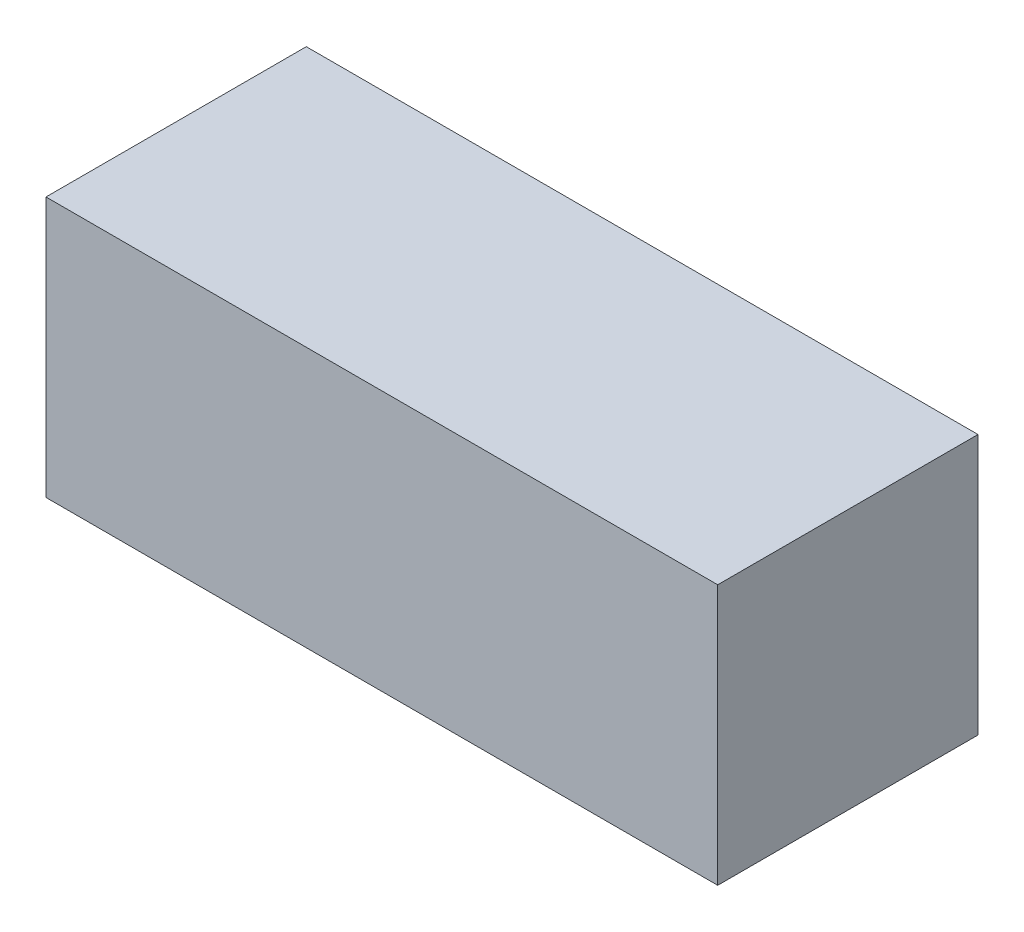
SolidWorks part; units mm, degrees
ref_plane "Front Plane" through (0, 0, 0) normal (0, 0, 1) x (1, 0, 0)
ref_plane "Top Plane" through (0, 0, 0) normal (0, 1, 0) x (1, 0, 0)
ref_plane "Right Plane" through (0, 0, 0) normal (1, 0, 0) x (0, 0, -1)
sketch "Sketch1" plane through (0, 0, 0) normal (0, 1, 0) x (1, 0, 0)
  line L1 (0, 1181.1) -> (6096, 1181.1)
  line L2 (0, 1181.1) -> (0, -1181.1)
  line L3 (0, -1181.1) -> (6096, -1181.1)
  line L4 (6096, 1181.1) -> (6096, -1181.1)
  dimension "D1" = 2362.2
  dimension "D2" = 6096
extrude "Extrude1" add sketch "Sketch1" along normal blind 2362.2
